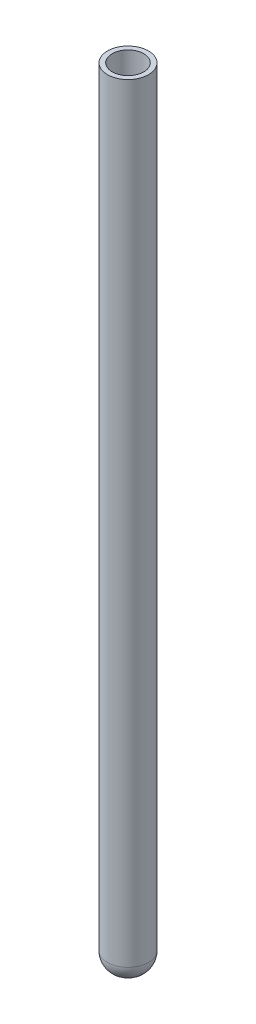
SolidWorks part; units mm, degrees
material "Nickel silver 65-12, UNS C75700"
ref_plane "Front" through (0, 0, 0) normal (0, 0, 1) x (1, 0, 0)
ref_plane "Top" through (0, 0, 0) normal (0, 1, 0) x (1, 0, 0)
ref_plane "Right" through (0, 0, 0) normal (1, 0, 0) x (0, 0, -1)
sketch "Sketch1" plane through (0, 0, 0) normal (1, 0, 0) x (0, 0, -1)
  line L0 (0.265, 0) -> (0.265, -10)
  line L1 (0.265, -10) -> (0, -10)
  line L2 (0, -10) -> (0, -13.21)
  line L3 (0, -13.21) -> (0.345, -13.21)
  line L8 (0.345, -13.21) -> (0.345, 0)
  line L11 (0.345, 0) -> (0.265, 0)
  dimension "D4" = 0.265
  dimension "D9" = 10
  dimension "D2" = 13.21
  dimension "D1" = 0.345
revolve "Revolve1" add sketch "Sketch1" angle 360 about L2
fillet "Fillet1" radius 0.3 1 edges at (0, -13.21, 0.345)
equation "\"D4@Sketch1\"=0.53/2"
equation "\"D1@Sketch1\"=0.69/2"
equation "\"D2@Sketch1\"=16.76-3.55"
